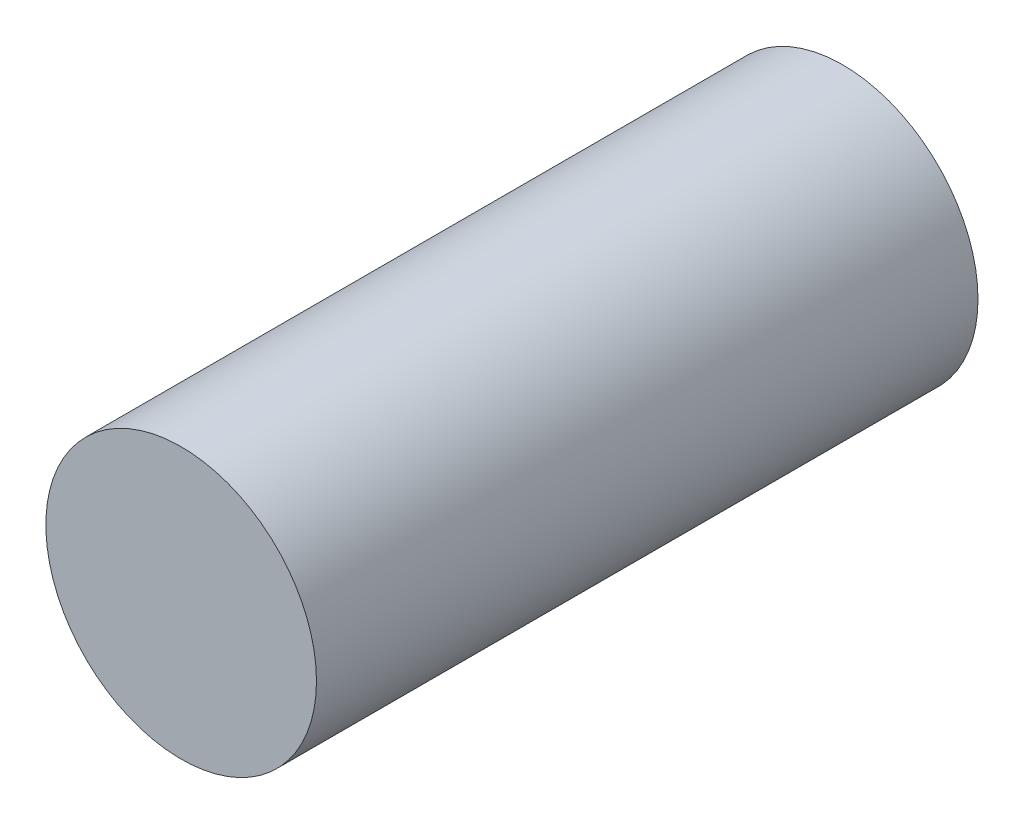
SolidWorks part; units mm, degrees
ref_plane "Front Plane" through (0, 0, 0) normal (0, 0, 1) x (1, 0, 0)
ref_plane "Top Plane" through (0, 0, 0) normal (0, 1, 0) x (1, 0, 0)
ref_plane "Right Plane" through (0, 0, 0) normal (1, 0, 0) x (0, 0, -1)
sketch "Sketch1" plane through (0, 0, 0) normal (0, 0, 1) x (1, 0, 0)
  circle A0 centre (0, 0) radius 4.5
extrude "Boss-Extrude1" add sketch "Sketch1" along normal blind 22
